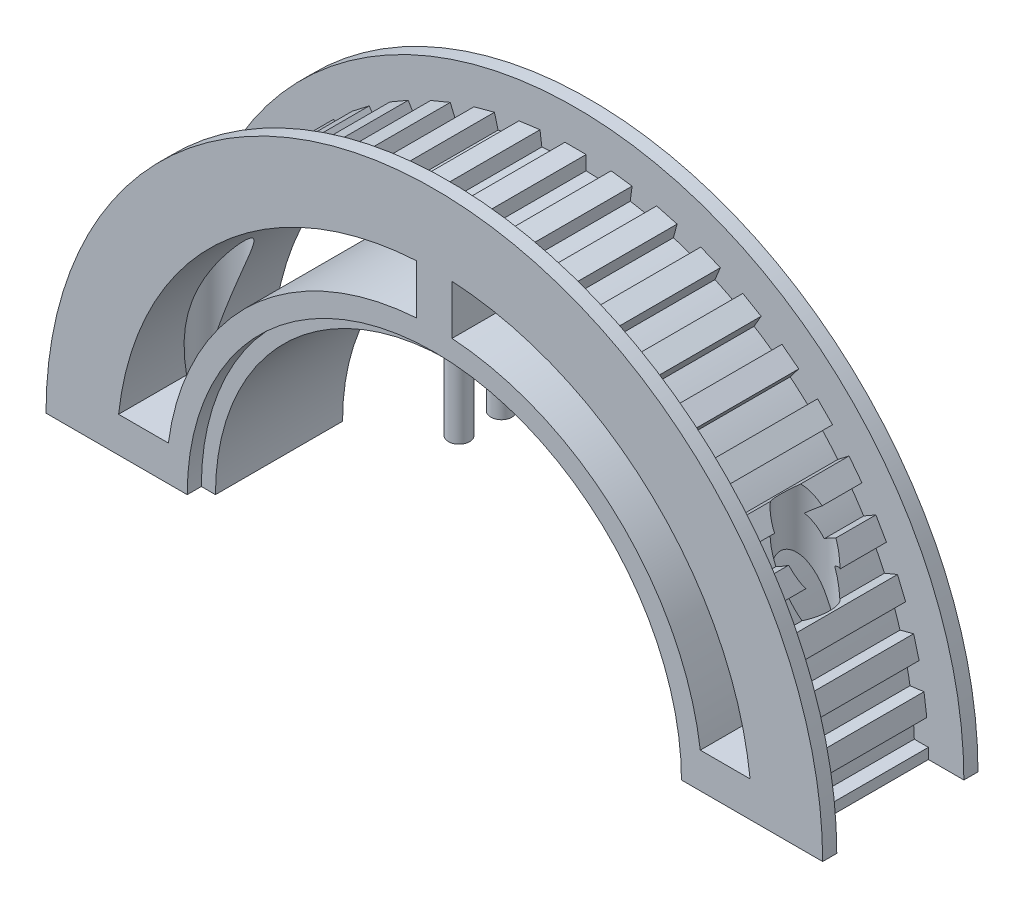
SolidWorks part; units mm, degrees
ref_plane "Front Plane" through (0, 0, 0) normal (0, 0, 1) x (1, 0, 0)
ref_plane "Top Plane" through (0, 0, 0) normal (0, 1, 0) x (1, 0, 0)
ref_plane "Right Plane" through (0, 0, 0) normal (1, 0, 0) x (0, 0, -1)
sketch "Sketch1" plane through (0, 0, 0) normal (0, 0, 1) x (1, 0, 0)
  line L0 (55, 0) -> (-55, 0) construction
  line L5 (0, -55) -> (0, 55) construction
  line L18 (-2.5, 36.9218) -> (2.5, 36.9218)
  line L19 (-2.5, 36.9218) -> (-2.5, 45.9218)
  line L20 (-2.5, 45.9218) -> (2.5, 45.9218)
  line L21 (2.5, 36.9218) -> (2.5, 45.9218)
  line L22 (-45, 0) -> (-48, 0)
  line L23 (45, 0) -> (48, 0)
  line L24 (4.775, 47.7619) -> (5.0361, 49.7448)
  line L29 (-1.5, 47.9766) -> (1.5, 47.9766)
  line L30 (-1.5, 47.9766) -> (-1.5, 49.9766)
  line L31 (-1.5, 49.9766) -> (1.5, 49.9766)
  line L32 (1.5, 47.9766) -> (1.5, 49.9766)
  line L33 (4.775, 47.7619) -> (7.7494, 47.3703)
  line L34 (7.7494, 47.3703) -> (8.0104, 49.3532)
  line L35 (5.0361, 49.7448) -> (8.0104, 49.3532)
  line L36 (10.9684, 46.73) -> (11.486, 48.6619)
  line L37 (10.9684, 46.73) -> (13.8661, 45.9536)
  line L38 (13.8661, 45.9536) -> (14.3838, 47.8854)
  line L39 (11.486, 48.6619) -> (14.3838, 47.8854)
  line L40 (16.974, 44.8986) -> (17.7394, 46.7463)
  line L41 (16.974, 44.8986) -> (19.7457, 43.7505)
  line L42 (19.7457, 43.7505) -> (20.511, 45.5983)
  line L43 (17.7394, 46.7463) -> (20.511, 45.5983)
  line L44 (22.6892, 42.2989) -> (23.6892, 44.031)
  line L45 (22.6892, 42.2989) -> (25.2873, 40.7989)
  line L46 (25.2873, 40.7989) -> (26.2873, 42.531)
  line L47 (23.6892, 44.031) -> (26.2873, 42.531)
  line L48 (28.0162, 38.9755) -> (29.2338, 40.5622)
  line L49 (28.0162, 38.9755) -> (30.3963, 37.1492)
  line L50 (30.3963, 37.1492) -> (31.6138, 38.7359)
  line L51 (29.2338, 40.5622) -> (31.6138, 38.7359)
  line L52 (32.8639, 34.9852) -> (34.2781, 36.3994)
  line L53 (32.8639, 34.9852) -> (34.9852, 32.8639)
  line L54 (34.9852, 32.8639) -> (36.3994, 34.2781)
  line L55 (34.2781, 36.3994) -> (36.3994, 34.2781)
  line L56 (37.1492, 30.3963) -> (38.7359, 31.6138)
  line L57 (37.1492, 30.3963) -> (38.9755, 28.0162)
  line L58 (38.9755, 28.0162) -> (40.5622, 29.2338)
  line L59 (38.7359, 31.6138) -> (40.5622, 29.2338)
  line L60 (40.7989, 25.2873) -> (42.531, 26.2873)
  line L61 (40.7989, 25.2873) -> (42.2989, 22.6892)
  line L62 (42.2989, 22.6892) -> (44.031, 23.6892)
  line L63 (42.531, 26.2873) -> (44.031, 23.6892)
  line L64 (43.7505, 19.7457) -> (45.5983, 20.511)
  line L65 (43.7505, 19.7457) -> (44.8986, 16.974)
  line L66 (44.8986, 16.974) -> (46.7463, 17.7394)
  line L67 (45.5983, 20.511) -> (46.7463, 17.7394)
  line L68 (45.9536, 13.8661) -> (47.8854, 14.3838)
  line L69 (45.9536, 13.8661) -> (46.73, 10.9684)
  line L70 (46.73, 10.9684) -> (48.6619, 11.486)
  line L71 (47.8854, 14.3838) -> (48.6619, 11.486)
  line L72 (47.3703, 7.7494) -> (49.3532, 8.0104)
  line L73 (47.3703, 7.7494) -> (47.7619, 4.775)
  line L74 (47.7619, 4.775) -> (49.7448, 5.0361)
  line L75 (49.3532, 8.0104) -> (49.7448, 5.0361)
  line L80 (-7.7494, 47.3703) -> (-8.0104, 49.3532)
  line L81 (-7.7494, 47.3703) -> (-4.775, 47.7619)
  line L82 (-4.775, 47.7619) -> (-5.0361, 49.7448)
  line L83 (-8.0104, 49.3532) -> (-5.0361, 49.7448)
  line L84 (-13.8661, 45.9536) -> (-14.3838, 47.8854)
  line L85 (-13.8661, 45.9536) -> (-10.9684, 46.73)
  line L86 (-10.9684, 46.73) -> (-11.486, 48.6619)
  line L87 (-14.3838, 47.8854) -> (-11.486, 48.6619)
  line L88 (-19.7457, 43.7505) -> (-20.511, 45.5983)
  line L89 (-19.7457, 43.7505) -> (-16.974, 44.8986)
  line L90 (-16.974, 44.8986) -> (-17.7394, 46.7463)
  line L91 (-20.511, 45.5983) -> (-17.7394, 46.7463)
  line L92 (-25.2873, 40.7989) -> (-26.2873, 42.531)
  line L93 (-25.2873, 40.7989) -> (-22.6892, 42.2989)
  line L94 (-22.6892, 42.2989) -> (-23.6892, 44.031)
  line L95 (-26.2873, 42.531) -> (-23.6892, 44.031)
  line L96 (-30.3963, 37.1492) -> (-31.6138, 38.7359)
  line L97 (-30.3963, 37.1492) -> (-28.0162, 38.9755)
  line L98 (-28.0162, 38.9755) -> (-29.2338, 40.5622)
  line L99 (-31.6138, 38.7359) -> (-29.2338, 40.5622)
  line L100 (-34.9852, 32.8639) -> (-36.3994, 34.2781)
  line L101 (-34.9852, 32.8639) -> (-32.8639, 34.9852)
  line L102 (-32.8639, 34.9852) -> (-34.2781, 36.3994)
  line L103 (-36.3994, 34.2781) -> (-34.2781, 36.3994)
  line L104 (-38.9755, 28.0162) -> (-40.5622, 29.2338)
  line L105 (-38.9755, 28.0162) -> (-37.1492, 30.3963)
  line L106 (-37.1492, 30.3963) -> (-38.7359, 31.6138)
  line L107 (-40.5622, 29.2338) -> (-38.7359, 31.6138)
  line L108 (-42.2989, 22.6892) -> (-44.031, 23.6892)
  line L109 (-42.2989, 22.6892) -> (-40.7989, 25.2873)
  line L110 (-40.7989, 25.2873) -> (-42.531, 26.2873)
  line L111 (-44.031, 23.6892) -> (-42.531, 26.2873)
  line L112 (-44.8986, 16.974) -> (-46.7463, 17.7394)
  line L113 (-44.8986, 16.974) -> (-43.7505, 19.7457)
  line L114 (-43.7505, 19.7457) -> (-45.5983, 20.511)
  line L115 (-46.7463, 17.7394) -> (-45.5983, 20.511)
  line L116 (-46.73, 10.9684) -> (-48.6619, 11.486)
  line L117 (-46.73, 10.9684) -> (-45.9536, 13.8661)
  line L118 (-45.9536, 13.8661) -> (-47.8854, 14.3838)
  line L119 (-48.6619, 11.486) -> (-47.8854, 14.3838)
  line L120 (-47.7619, 4.775) -> (-49.7448, 5.0361)
  line L121 (-47.7619, 4.775) -> (-47.3703, 7.7494)
  line L122 (-47.3703, 7.7494) -> (-49.3532, 8.0104)
  line L123 (-49.7448, 5.0361) -> (-49.3532, 8.0104)
  line L128 (-47.9766, -1.5) -> (-49.9766, -1.5) [skipped]
  line L129 (-49.9766, -1.5) -> (-49.9766, 1.5) [skipped]
  line L130 (-47.9766, 1.5) -> (-49.9766, 1.5) [skipped]
  line L131 (-47.9766, -1.5) -> (-47.9766, 1.5) [skipped]
  line L132 (47.9766, 1.5) -> (49.9766, 1.5) [skipped]
  line L133 (49.9766, 1.5) -> (49.9766, -1.5) [skipped]
  line L134 (47.9766, -1.5) -> (49.9766, -1.5) [skipped]
  line L135 (47.9766, 1.5) -> (47.9766, -1.5) [skipped]
  line L136 (-38, 0) -> (-35, 0)
  line L137 (47.9766, 1.5) -> (49.9766, 1.5)
  line L138 (47.9766, 1.5) -> (47.9766, 0)
  line L139 (47.9766, 0) -> (49.9766, 0)
  line L140 (49.9766, 1.5) -> (49.9766, 0)
  line L141 (-47.9766, 1.5) -> (-49.9766, 1.5)
  line L142 (-47.9766, 1.5) -> (-47.9766, 0)
  line L143 (-47.9766, 0) -> (-49.9766, 0)
  line L144 (-49.9766, 1.5) -> (-49.9766, 0)
  line L145 (35, 0) -> (38, 0)
  line L147 (-45, 0) -> (-37.4718, 0)
  line L148 (-45, 0) -> (-45, 5)
  line L149 (-45, 5) -> (-37.4718, 5)
  line L150 (-37.4718, 0) -> (-37.4718, 5)
  line L151 (45, 0) -> (37.3745, 0)
  line L152 (45, 0) -> (45, 5)
  line L153 (45, 5) -> (37.3745, 5)
  line L154 (37.3745, 0) -> (37.3745, 5)
  arc A2 (-35, 0) -> (35, 0) centre (0, 0) cw
  arc A4 (45, 0) -> (-45, 0) centre (0, 0) ccw
  arc A5 (48, 0) -> (-48, 0) centre (0, 0) ccw
  arc A6 (38, 0) -> (-38, 0) centre (0, 0) ccw
  point P81 (0, 0)
  point P131 (0, 0)
  dimension "D4" = 5
  dimension "D5" = 35
  dimension "D15" = 2
  dimension "D3" = 48
  dimension "D6" = 38
  dimension "D2" = 3
  dimension "D7" = 5
  dimension "D11" = 5
  dimension "D12" = 2.5
  dimension "D14" = 9
  dimension "D16" = 3
  dimension "D17" = 1.5
  dimension "D20" = 1.5
  dimension "D21" = 2
  dimension "D22" = 2
  dimension "D23" = 1.5
  dimension "D18" = 13
  dimension "D19" = 13
extrude "Boss-Extrude1" add sketch "Sketch1" along normal blind 22
sketch "Sketch10" plane through (0, 0, 0) normal (0, -1, 0) x (-1, 0, 0)
  line L0 (35, -22) -> (35, 0) construction
  line L1 (35, -22) -> (49.9766, -22) construction
  circle A0 centre (41.5, -11) radius 1.75
  dimension "D3" = 3.5
  dimension "D1" = 6.5
  dimension "D2" = 11
extrude "Cut-Extrude4" cut sketch "Sketch10" against normal through all
mirror "Mirror4" about plane through (0, 0, 0) normal (1, 0, 0) of "Cut-Extrude4"
sketch "Sketch5" plane through (0, 0, 0) normal (0, 0, 1) x (1, 0, 0)
  line L0 (55, 0) -> (-55, 0) construction
  line L1 (-48, 0) -> (-55, 0)
  line L2 (48, 0) -> (55, 0)
  arc A0 (48, 0) -> (-48, 0) centre (0, 0) ccw
  circle A1 centre (0, 0) radius 48 construction
  arc A2 (55, 0) -> (-55, 0) centre (0, 0) ccw
  dimension "D1" = 55
  dimension "D2" = 7
extrude "Boss-Extrude3" add sketch "Sketch5" along normal blind 2
sketch "Sketch6" plane through (0, 0, 22) normal (0, 0, 1) x (1, 0, 0)
  line L0 (55, 0) -> (-55, 0) construction
  line L1 (-45, 0) -> (-55, 0)
  line L2 (45, 0) -> (55, 0)
  arc A0 (55, 0) -> (-55, 0) centre (0, 0) ccw
  arc A1 (45, 0) -> (-45, 0) centre (0, 0) ccw
  dimension "D1" = 55
  dimension "D2" = 45
extrude "Boss-Extrude4" add sketch "Sketch6" against normal blind 2
ref_plane "Plane1" through (0, 0, 2) normal (0, 0, 1) x (1, 0, 0)
sketch "Sketch7" plane through (0, 0, 2) normal (0, 0, 1) x (1, 0, 0)
  line L0 (55, 0) -> (-55, 0) construction
  line L1 (-35, 0) -> (-33, 0)
  line L2 (33, 0) -> (35, 0)
  arc A0 (35, 0) -> (-35, 0) centre (0, 0) ccw
  arc A1 (33, 0) -> (-33, 0) centre (0, 0) ccw
  dimension "D1" = 35
  dimension "D2" = 33
extrude "Boss-Extrude5" add sketch "Sketch7" along normal blind 18
sketch "Sketch11" plane through (0, 5, 0) normal (0, 1, 0) x (1, 0, 0)
  circle A0 centre (-41.5, -11) radius 3.5
  dimension "D1" = 7
extrude "Cut-Extrude5" cut sketch "Sketch11" along normal through all
mirror "Mirror5" about plane through (0, 0, 0) normal (1, 0, 0) of "Cut-Extrude5"
ref_plane "Plane2" through (0, 33, 0) normal (0, -1, 0) x (-1, 0, 0)
sketch "Sketch14" plane through (0, 33, 0) normal (0, -1, 0) x (-1, 0, 0)
  line L0 (-35, -20) -> (35, -20) construction
  circle A0 centre (0, -18.5) radius 1.5
  circle A1 centre (0, -12.5) radius 1.5
  point P6 (0, 0)
  point P7 (0, 0)
  dimension "D1" = 3
  dimension "D3" = 3
  dimension "D2" = 1.5
  dimension "D4" = 6
extrude "Boss-Extrude6" add sketch "Sketch14" along normal blind 10
sketch "Sketch15" plane through (0, 5, 0) normal (0, 1, 0) x (1, 0, 0)
  line L1 (-41.5, -14.1754) -> (-38.75, -12.5877)
  line L2 (-38.75, -12.5877) -> (-38.75, -9.4123)
  line L3 (-38.75, -9.4123) -> (-41.5, -7.8246)
  line L4 (-41.5, -7.8246) -> (-44.25, -9.4123)
  line L5 (-44.25, -9.4123) -> (-44.25, -12.5877)
  line L6 (-44.25, -12.5877) -> (-41.5, -14.1754)
  circle A0 centre (-41.5, -11) radius 2.75 construction
  dimension "D1" = 5.5
extrude "Cut-Extrude8" cut sketch "Sketch15" against normal blind 2
